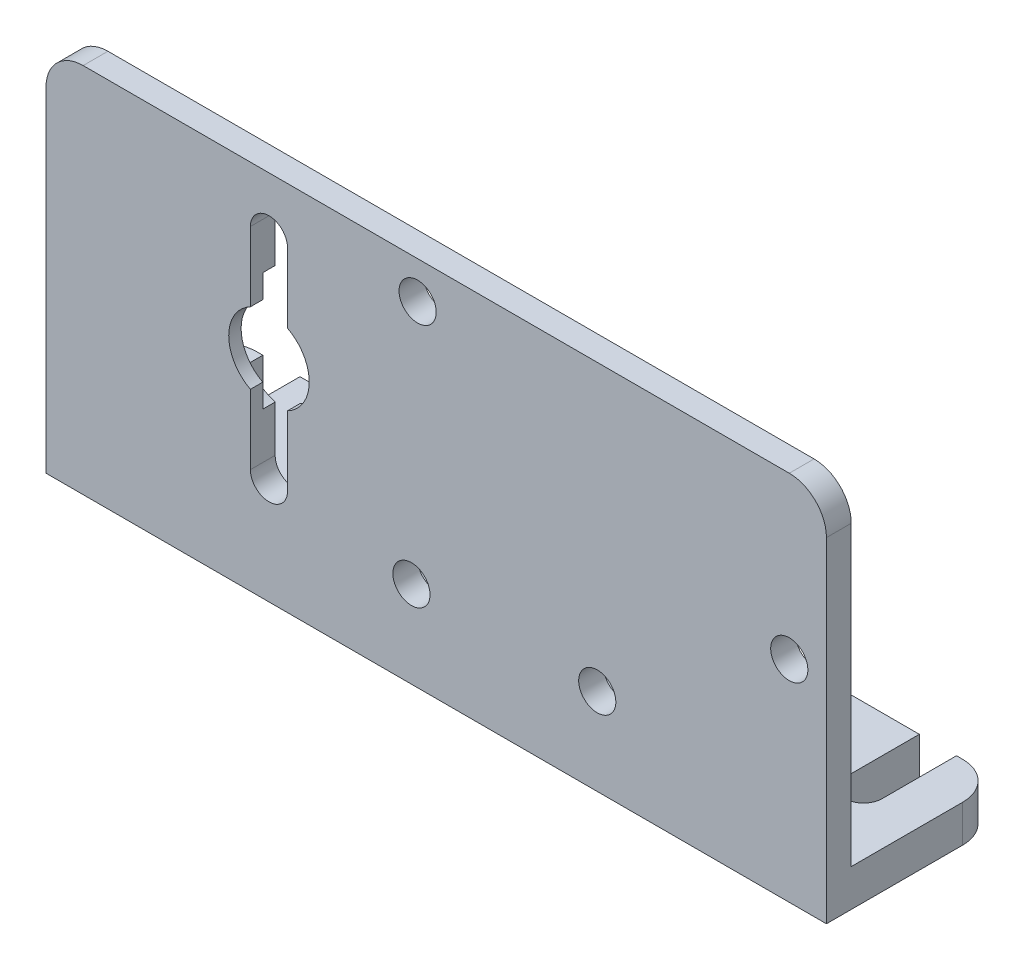
SolidWorks part; units mm, degrees
material "PVC 0.007 Plasticized"
ref_plane "Front Plane" through (0, 0, 0) normal (0, 0, 1) x (1, 0, 0)
ref_plane "Top Plane" through (0, 0, 0) normal (0, 1, 0) x (1, 0, 0)
ref_plane "Right Plane" through (0, 0, 0) normal (1, 0, 0) x (0, 0, -1)
sketch "Sketch1" plane through (0, 0, 0) normal (0, 0, 1) x (1, 0, 0)
  line L1 (31.5, 15) -> (-31.5, 15)
  line L2 (31.5, 15) -> (31.5, -15)
  line L3 (31.5, -15) -> (-31.5, -15)
  line L4 (-31.5, 15) -> (-31.5, -15)
  line L5 (31.5, 15) -> (-31.5, -15) construction
  line L6 (31.5, -15) -> (-31.5, 15) construction
  point P0 (0, 0)
  dimension "D1" = 63
  dimension "D2" = 30
extrude "Boss-Extrude1" add sketch "Sketch1" along normal blind 2
sketch "Sketch2" plane through (0, 0, 0) normal (0, 0, 1) x (1, 0, 0)
  line L0 (31.5, -15) -> (31.5, 15) construction
  line L1 (-31.5, -15) -> (31.5, -15)
  line L2 (-31.5, -15) -> (-31.5, -12)
  line L3 (-31.5, -12) -> (31.5, -12)
  line L4 (31.5, -15) -> (31.5, -12)
  dimension "D1" = 3
extrude "Boss-Extrude2" add sketch "Sketch2" against normal blind 12
sketch "Sketch3" plane through (0, -12, 0) normal (0, 1, 0) x (1, 0, 0)
  line L0 (26.5, 6) -> (26.5, 18) construction
  line L1 (31.5, 12) -> (-31.5, 12) construction
  line L2 (25, 6) -> (25, 18)
  line L3 (28, 6) -> (28, 18)
  line L4 (0, 0) -> (0, 12) construction
  line L5 (-26.5, 6) -> (-26.5, 18) construction
  line L6 (-25, 6) -> (-25, 18)
  line L7 (-28, 6) -> (-28, 18)
  line L10 (31.5, 12) -> (-31.5, 12) construction
  arc A0 (25, 6) -> (28, 6) centre (26.5, 6) ccw
  arc A1 (28, 18) -> (25, 18) centre (26.5, 18) ccw
  arc A2 (-25, 6) -> (-28, 6) centre (-26.5, 6) cw
  arc A3 (-28, 18) -> (-25, 18) centre (-26.5, 18) cw
  point P4 (26.5, 12)
  point P9 (25, 12)
  point P15 (-26.5, 12)
  dimension "D1" = 7.5
  dimension "D2" = 3
  dimension "D3" = 53
extrude "Cut-Extrude1" cut sketch "Sketch3" against normal through all
fillet "Fillet1" radius 3 4 edges at (-31.5, 15, 1) (31.5, 15, 1) (-31.5, -13.5, -12) (31.5, -13.5, -12)
sketch "Sketch4" plane through (0, 0, 2) normal (0, 0, 1) x (1, 0, 0)
  line L0 (-13.5, 10.5) -> (-13.5, -6.5) construction
  line L1 (-12, 10.5) -> (-12, -6.5)
  line L2 (-15, 10.5) -> (-15, -6.5)
  line L3 (-31.5, 12) -> (-31.5, -15) construction
  line L4 (28.5, 15) -> (-28.5, 15) construction
  arc A0 (-12, 10.5) -> (-15, 10.5) centre (-13.5, 10.5) ccw
  arc A1 (-15, -6.5) -> (-12, -6.5) centre (-13.5, -6.5) ccw
  point P2 (-13.5, 2)
  dimension "D2" = 20
  dimension "D1" = 3
  dimension "D3" = 18
  dimension "D4" = 4.5
extrude "Cut-Extrude2" cut sketch "Sketch4" against normal through all
sketch "Sketch5" plane through (0, 0, 0) normal (0, 0, 1) x (1, 0, 0)
  line L0 (-12, 2) -> (-13.5, 2) construction
  line L1 (-12, -6.5) -> (-12, 10.5) construction
  line L2 (-15, 2) -> (-13.5, 2) construction
  line L3 (-15, 10.5) -> (-15, -6.5) construction
  circle A0 centre (-13.5, 2) radius 5
  dimension "D1" = 10
extrude "Cut-Extrude3" cut sketch "Sketch5" along normal blind 1
sketch "Sketch6" plane through (0, 0, 1) normal (0, 0, -1) x (-1, 0, 0)
  circle A0 centre (13.5, 2) radius 3.25
  dimension "D1" = 6.5
extrude "Cut-Extrude4" cut sketch "Sketch6" against normal through all
sketch "Sketch7" plane through (0, 0, 2) normal (0, 0, 1) x (1, 0, 0)
  line L0 (-13.5, 2) -> (28.5, 2) construction
  line L1 (28.5, 2) -> (31.5, 2) construction
  line L2 (-31.5, 12) -> (-31.5, -15) construction
  line L3 (-31.5, 12) -> (-1.5, 12) construction
  line L4 (28.5, 15) -> (-28.5, 15) construction
  line L5 (31.5, -15) -> (31.5, 12) construction
  line L6 (31.5, -8) -> (13, -8) construction
  line L7 (13, -8) -> (-2, -8) construction
  line L8 (31.5, -12) -> (-31.5, -12) construction
  circle A0 centre (28.5, 2) radius 1.5
  circle A1 centre (-1.5, 12) radius 1.5
  circle A2 centre (-2, -8) radius 1.5
  circle A3 centre (13, -8) radius 1.5
  dimension "D1" = 3
  dimension "D4" = 3
  dimension "D6" = 3
  dimension "D7" = 3
  dimension "D2" = 3
  dimension "D3" = 30
  dimension "D5" = 3
  dimension "D8" = 18.5
  dimension "D9" = 4
  dimension "D10" = 15
extrude "Cut-Extrude5" cut sketch "Sketch7" against normal through all
